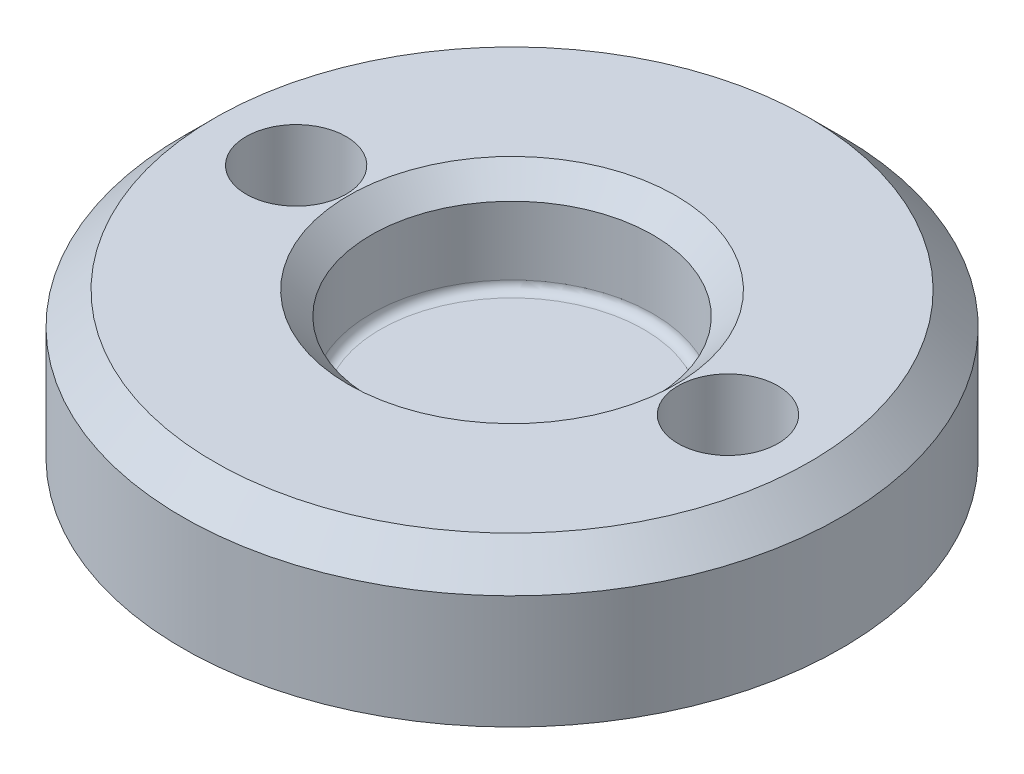
SolidWorks part; units mm, degrees
material "Brass"
ref_plane "Front Plane" through (0, 0, 0) normal (0, 0, 1) x (1, 0, 0)
ref_plane "Top Plane" through (0, 0, 0) normal (0, 1, 0) x (1, 0, 0)
ref_plane "Right Plane" through (0, 0, 0) normal (1, 0, 0) x (0, 0, -1)
sketch "Sketch1" plane through (0, 0, 0) normal (0, 0, 1) x (1, 0, 0)
  line L0 (0, 0) -> (0, 7.0462) construction
  line L1 (0, 0) -> (-7.25, 0)
  line L2 (-7.25, 0) -> (-7.25, 3.2)
  line L3 (-7.25, 3.2) -> (-3.1, 3.2)
  line L4 (-3.1, 3.2) -> (-3.1, 1)
  line L5 (-3.1, 1) -> (0, 1)
  line L6 (0, 0) -> (0, 1)
  dimension "D1" = 3.1
  dimension "D2" = 4.15
  dimension "D3" = 1
  dimension "D4" = 2.2
  dimension "D5" = 7.25
revolve "Revolve1" add sketch "Sketch1" angle 360 about L0
chamfer "Chamfer2" distance 0.5 angle 45 1 edges at (0, 3.2, -3.1)
sketch "Sketch2" plane through (0, 3.2, 0) normal (0, 1, 0) x (1, 0, 0)
  line L0 (-6.8053, -2.5) -> (-12.25, -2.5)
  line L1 (-12.25, -2.5) -> (-12.25, 2.5)
  line L2 (-12.25, 2.5) -> (-6.8053, 2.5)
  line L3 (-12.25, 0) -> (-7.25, 0) construction
  circle A0 centre (0, 0) radius 7.25 construction
  arc A1 (-6.8053, 2.5) -> (-6.8053, -2.5) centre (0, 0) ccw
  point P2 (-12.25, 0)
  dimension "D1" = 5
extrude "Boss-Extrude1" [suppressed] add sketch "Sketch2" against normal up to surface (3 mm away)
hole_wizard "CSK for M2 Flat Head Machine Screw1" positions "Sketch3" profile "Sketch4" countersink size "M2" standard "ANSI Metric"
sketch "Sketch3" plane through (0, 0, 0) normal (0, -1, 0) x (-1, 0, 0)
  point P0 (4.75, 0)
  dimension "D1" = 4.75
sketch "Sketch4" plane through (-4.75, 0, 0) normal (1, 0, 0) x (0, 0, -1)
  line L0 (0, 0) -> (0, 5.6609)
  line L1 (0, 5.6609) -> (1.1, 5)
  line L2 (1.1, 5) -> (1.1, 1.1)
  line L3 (1.1, 1.1) -> (2.2, 0)
  line L5 (2.2, 0) -> (0, 0)
  line L6 (-1.1, 1.1) -> (-2.2, 0) construction
  line L10 (0, 5.6609) -> (-1.1, 5) construction
  line L11 (0, -6.35) -> (0, 107.95) construction
  dimension "Hole Dia." = 2.2
  dimension "Hole Depth" = 5
  dimension "Near C'Sink Dia." = 4.4
  dimension "Near C'Sink Angle" = 90
  dimension "Drill Angle" = 118
sketch "Sketch5" [suppressed] plane through (0, 0, 0) normal (0, -1, 0) x (1, 0, 0)
  line L1 (-6.8053, 2.5) -> (-12.25, 2.5) construction
  line L2 (-6.8053, 2.5) -> (-12.25, 2.5) construction
  line L3 (-12.25, -2.5) -> (-6.8053, -2.5) construction
  line L4 (-4.75, -2.5) -> (-12.25, -2.5)
  line L5 (-12.25, -2.5) -> (-12.25, 2.5)
  line L9 (-12.25, 2.5) -> (-4.75, 2.5)
  arc A0 (-4.75, -2.5) -> (-4.75, 2.5) centre (-4.75, 0) cw
extrude "Cut-Extrude1" [suppressed] cut sketch "Sketch5" against normal through all both and the other way through all
pattern_circular "CirPattern1" count 2 over 360 about axis through (0, 0, 0) along (0, 1, 0) of "CSK for M2 Flat Head Machine Screw1", "Boss-Extrude1", "Cut-Extrude1"
fillet "Fillet1" [suppressed] radius 10
chamfer "Chamfer3" distance 0.7 angle 45 1 edges at (0, 3.2, -7.25)
fillet "Fillet2" radius 0.2 1 edges at (0, 1, -3.1)
